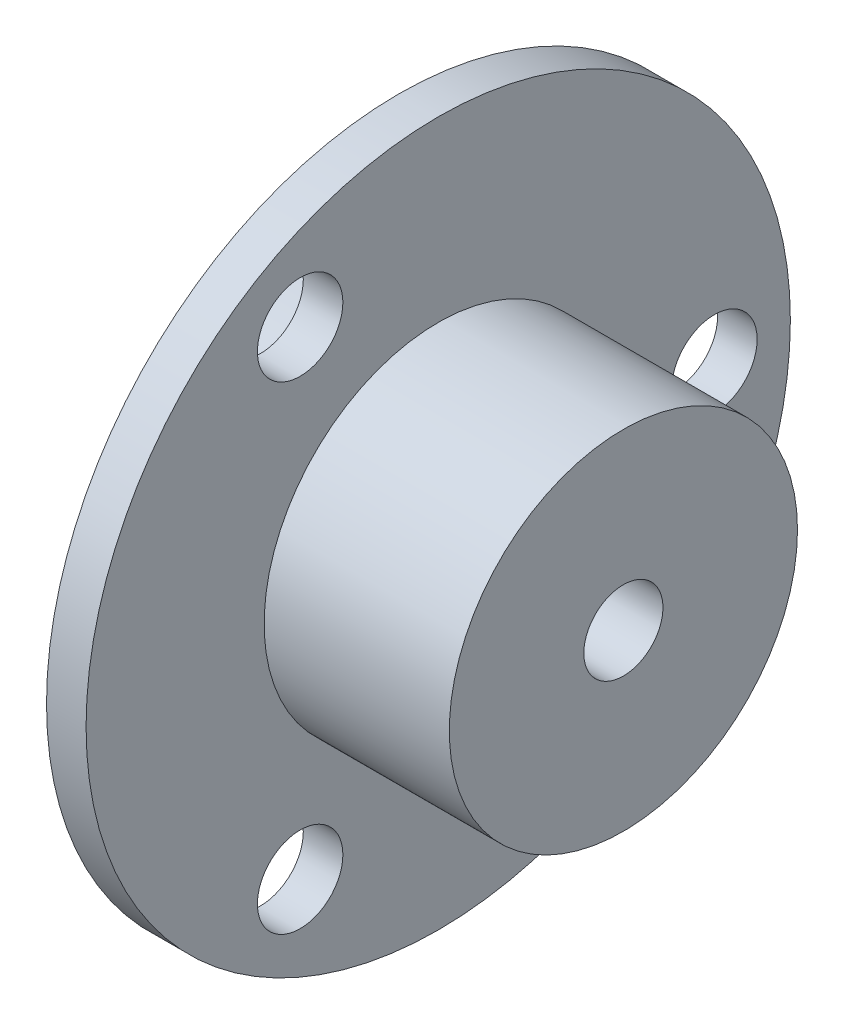
SolidWorks part; units mm, degrees
ref_plane "Front Plane" through (0, 0, 0) normal (0, 0, 1) x (1, 0, 0)
ref_plane "Top Plane" through (0, 0, 0) normal (0, 1, 0) x (1, 0, 0)
ref_plane "Right Plane" through (0, 0, 0) normal (1, 0, 0) x (0, 0, -1)
sketch "Sketch1" plane through (0, 0, 0) normal (1, 0, 0) x (0, 0, -1)
  circle A0 centre (0, 0) radius 22.25
  dimension "D1" = 44.5
extrude "Boss-Extrude1" add sketch "Sketch1" along normal blind 2.5
sketch "Sketch2" plane through (2.5, 0, 0) normal (1, 0, 0) x (0, 0, -1)
  line L0 (-30.5097, 0) -> (28.5834, 0) construction
  line L1 (0, 23.6435) -> (0, -23.9542) construction
  line L2 (-8.725, 15.1121) -> (0, 0) construction
  line L3 (-8.725, -15.1121) -> (0, 0) construction
  circle A0 centre (0, 0) radius 17.45
  circle A1 centre (17.45, 0) radius 2.7
  circle A2 centre (-8.725, 15.1121) radius 2.7
  circle A3 centre (-8.725, -15.1121) radius 2.7
  dimension "D1" = 34.9
  dimension "D2" = 5.4
  dimension "D3" = 60
  dimension "D4" = 60
extrude "Cut-Extrude1" cut sketch "Sketch2" against normal through all contours A0 A2 | A0 A2 | A0 A1 | A0 A1 | A0 A3 | A0 A3
sketch "Sketch3" plane through (2.5, 0, 0) normal (1, 0, 0) x (0, 0, -1)
  circle A0 centre (0, 0) radius 11
  dimension "D1" = 22
extrude "Boss-Extrude2" add sketch "Sketch3" along normal blind 19 from offset 7.3 offset against normal yes
sketch "Sketch4" plane through (-4.8, 0, 0) normal (-1, 0, 0) x (0, 0, 1)
  circle A0 centre (0, 0) radius 2.5
  dimension "D1" = 5
extrude "Cut-Extrude2" cut sketch "Sketch4" against normal through all contours A0
